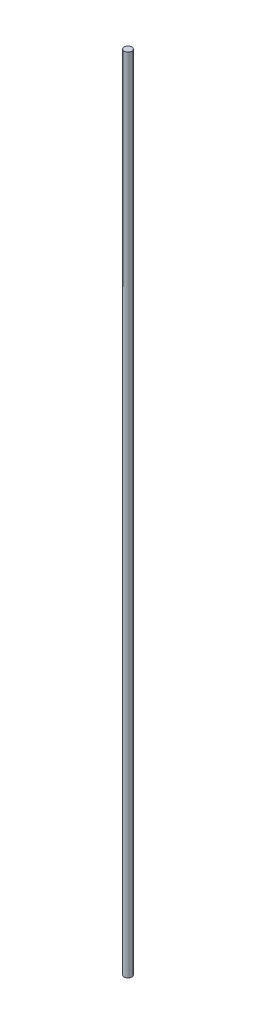
SolidWorks part; units mm, degrees
ref_plane "Спереди" through (0, 0, 0) normal (0, 0, 1) x (1, 0, 0)
ref_plane "Сверху" through (0, 0, 0) normal (0, 1, 0) x (1, 0, 0)
ref_plane "Справа" through (0, 0, 0) normal (1, 0, 0) x (0, 0, -1)
sketch "Эскиз2" plane through (0, 0, 0) normal (0, 0, 1) x (1, 0, 0)
  line L0 (0, 350.0223) -> (-5, 350.0223) construction
  line L5 (-2.5, 350.0223) -> (0, 350.0223)
  line L6 (-2.5, 350.0223) -> (-2.5, -179.3777)
  line L7 (-2.5, -179.3777) -> (0, -179.3777)
  line L8 (0, 350.0223) -> (0, -179.3777)
  line L9 (-2.5, 350.0223) -> (0, -179.3777) construction
  line L10 (-2.5, -179.3777) -> (0, 350.0223) construction
  line L13 (-25.8353, -179.3777) -> (28.1755, -179.3777) construction
  point P0 (-1.25, 85.3223)
  point P12 (0, 0)
  dimension "D1" = 2.5
revolve "Повернуть1" add sketch "Эскиз2" angle 360 about L6
equation "\"Ширина груза\"= 160"
equation "\"Глубина груза\"= 240"
equation "\"Высота груза\"= 160"
equation "\"Ширина ячейки\"= \"Ширина груза\" + 10"
equation "\"Глубина ячейки\"= \"Глубина груза\" + 10"
equation "\"Высота ячейки\"= \"Высота груза\" + 10 + 13"
equation "\"Колво ячеек ширина\"= 2"
equation "\"Колво ячеек высота\"= 2"
equation "\"Толщина стенки\" = \"Толщина тонких панелей\""
equation "\"Крепление дверцы\"= 5 "
equation "\"Ширина рейки\"= \"Толщина шестерни\""
equation "\"Высота рейки\"= 20"
equation "\"Высота пола\" = 2*\"Толщина тонких панелей\""
equation "\"Колво полозьев\"= 5"
equation "\"Отступ рейки\"= 20"
equation "\"Глубина каретки\"= \"Глубина ячейки\" + 30 + \"Мотор Y высота корпуса\" + 20"
equation "\"Длинна рейки\" = (\"Ширина ячейки\"+\"Толщина вертикальных стенок\"+\"Крепление дверцы\")*\"Колво ячеек ширина\"+\"Ширина ячейки выгрузки\"*\"Колво выгрузки\"+\"Толщина вертикальных стенок\"+2*\"Отступ крепления мотора фиксации\"-\"Крепление дверцы\"*\"Колво ячеек ширина\""
equation "\"Отступ шпильки\"= 26"
equation "\"Диаметр шпильки\"= 5"
equation "\"Длинна шпильки\" = (\"Высота ячейки\"+\"Толщина горизонтальных плит\"+\"Высота пола\")*\"Колво ячеек высота\"+2*(\"Толщина горизонтальных плит\"+\"Отступ рейки\")"
equation "\"D1@Эскиз2\"= \"Диаметр шпильки\" / 2"
equation "\"Ширина пластины\"= 50  "
equation "\"Высота зона выгрузки\"= \"Высота ячейки\" * 2 + \"Толщина стенки\" * 2"
equation "\"Колво выгрузки\"= 1"
equation "\"Отступ крепления мотора фиксации\" = (\"Ширина пластины\"+20-\"Толщина вертикальных стенок\")/2"
equation "\"Мотор X ширина корпуса\"= 42.3"
equation "\"Мотор X высота корпуса\"= 42.3"
equation "\"Мотор X длина корпуса\"= 40"
equation "\"Мотор X вылет вала\"= 19.8"
equation "\"Мотор Y ширина корпуса\"= 42.3"
equation "\"Мотор Y высота корпуса\"= 42.3"
equation "\"Мотор Y длина корпуса\"= 48"
equation "\"Мотор Y вылет вала\"= 30"
equation "\"Мотор Z ширина корпуса\"= 42"
equation "\"Мотор Z высота корпуса\"= 42"
equation "\"Мотор Z длина корпуса\"= 40"
equation "\"Мотор Z вылет вала\"= 23"
equation "\"Мотор диаметр вала ПРЕДВ\"= 5"
equation "\"Мотор шаг крепления ПРЕДВ\"= 31"
equation "\"Мотор диаметр отверстий ПРЕДВ\"= 3"
equation "\"Мотор глубина отверстий ПРЕДВ\"= 4.5"
equation "\"Мотор диаметр буртика ПРЕДВ\"= 22"
equation "\"Мотор высота буртика ПРЕДВ\"= 2"
equation "\"Мотор диаметр шкива ПРЕДВ\"= 16"
equation "\"Мотор длина шкива ПРЕДВ\"= 12"
equation "\"Мотор отступ шкива ПРЕДВ\"= 5"
equation "\"Мотор X шаг градусов\"= 1.8"
equation "\"Мотор X ток А\"= 1.5"
equation "\"Мотор X сопротивление Ом\"= 1.3"
equation "\"Мотор X индуктивность мГн\"= 2"
equation "\"Мотор Y шаг градусов\"= 1.8"
equation "\"Мотор Y ток А\"= 2.2"
equation "\"Мотор Y сопротивление Ом\"= 0.9"
equation "\"Мотор Y индуктивность мГн\"= 2"
equation "\"Мотор Z шаг градусов\"= 1.8"
equation "\"Мотор Z ток А\"= 1"
equation "\"Мотор Z сопротивление Ом\"= 4"
equation "\"Мотор Z индуктивность мГн\"= 8"
equation "\"Мотор Y диаметр ротора\"= 25.78"
equation "\"Ширина ячейки выгрузки\" = \"Ширина ячейки\"+\"Толщина вертикальных стенок\"+2*\"Отступ крепления мотора фиксации\""
equation "\"Толщина тонких панелей\" = 6"
equation "\"Толщина вертикальных стенок\" = 6"
equation "\"Толщина горизонтальных плит\" = 6"
equation "\"Базовая высота корпуса\"= (\"Высота ячейки\"+\"Толщина тонких панелей\"+\"Высота пола\")*\"Колво ячеек высота\"+6*\"Толщина тонких панелей\"+\"Мотор X ширина корпуса\"+\"Мотор Y ширина корпуса\"+75"
equation "\"Высота корпуса\"= (\"Высота ячейки\"+\"Толщина горизонтальных плит\"+\"Высота пола\")*\"Колво ячеек высота\"+2*\"Толщина горизонтальных плит\"+4*\"Толщина тонких панелей\"+\"Мотор X ширина корпуса\"+\"Мотор Y ширина корпуса\"+75"
equation "\"Смещение центра корпуса\"= (\"Высота корпуса\"-\"Базовая высота корпуса\")/2-(\"Толщина горизонтальных плит\"-\"Толщина тонких панелей\")"
equation "\"Отметка пола\"= -\"Базовая высота корпуса\"/2+\"Толщина тонких панелей\""
equation "\"Отметка потолка\"= \"Отметка пола\"+\"Высота корпуса\"-2*\"Толщина горизонтальных плит\""
equation "\"Отметка верхней полки\"= \"Отметка потолка\"-(28+\"Толщина тонких панелей\")-\"Высота ячейки\"-\"Высота пола\""
equation "\"Отметка нижней полки\"= \"Отметка верхней полки\"-\"Высота ячейки\"-\"Высота пола\"-\"Толщина горизонтальных плит\""
equation "\"Толщина шестерни\"= 10"
